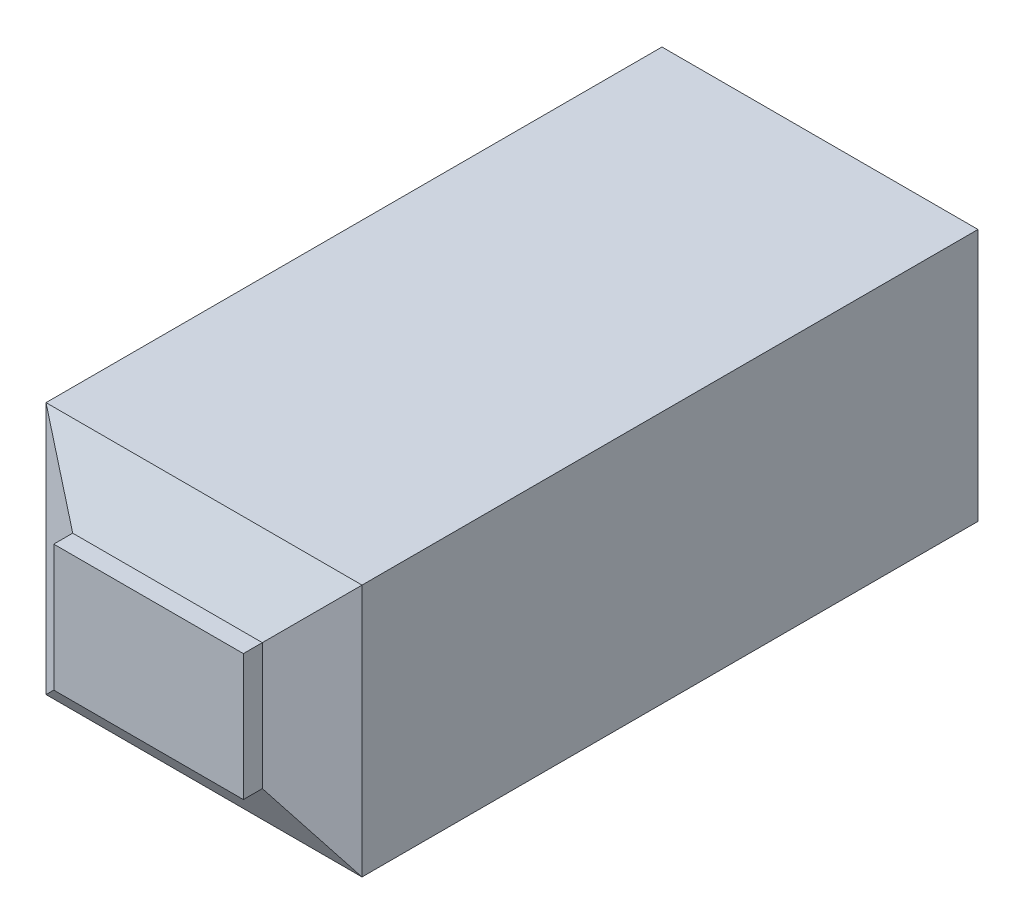
SolidWorks part; units mm, degrees
material "1.0553 (S355J0)"
ref_plane "Front Plane" through (0, 0, 0) normal (0, 0, 1) x (1, 0, 0)
ref_plane "Top Plane" through (0, 0, 0) normal (0, 1, 0) x (1, 0, 0)
ref_plane "Right Plane" through (0, 0, 0) normal (1, 0, 0) x (0, 0, -1)
sketch "Sketch1" plane through (0, 0, 0) normal (0, 0, 1) x (1, 0, 0)
  line L1 (-25, -20) -> (25, -20)
  line L2 (-25, -20) -> (-25, 20)
  line L3 (-25, 20) -> (25, 20)
  line L4 (25, -20) -> (25, 20)
  line L5 (-25, -20) -> (25, 20) construction
  line L6 (-25, 20) -> (25, -20) construction
  point P0 (0, 0)
  dimension "D1" = 50
  dimension "D2" = 40
extrude "Boss-Extrude1" add sketch "Sketch1" against normal blind 115
sketch "Sketch2" plane through (0, 0, 0) normal (0, 0, 1) x (1, 0, 0)
  line L1 (-15, -10) -> (15, -10)
  line L2 (-15, -10) -> (-15, 10)
  line L3 (-15, 10) -> (15, 10)
  line L4 (15, -10) -> (15, 10)
  line L5 (-15, -10) -> (15, 10) construction
  line L6 (-15, 10) -> (15, -10) construction
  point P0 (0, 0)
  point P5 (0, 0)
  point P6 (0, 0)
  dimension "D1" = 30
  dimension "D2" = 20
ref_plane "Plane1" through (15, 10, 0) normal (1, 0, 0) x (0, 0, -1)
sketch "Sketch3" plane through (15, 10, 0) normal (1, 0, 0) x (0, 0, -1)
  line L0 (115, 10) -> (0, 10) construction
  line L1 (0, -30) -> (0, 10) construction
  line L2 (8.7735, 10) -> (0, 10)
  line L3 (0, 0) -> (0, 10)
  line L4 (0, 0) -> (3, 0)
  line L5 (3, 0) -> (8.7735, 10)
  dimension "D1" = 10
  dimension "D2" = 60
  dimension "D3" = 3
sweep "Cut-Sweep1" cut profiles "Sketch3" path "Sketch2"
ref_plane "MirrorPlane" through (0, 0, -57.5) normal (0, 0, 1) x (1, 0, 0)
mirror "Mirror1" about plane through (0, 0, -57.5) normal (0, 0, 1) of "Cut-Sweep1"
